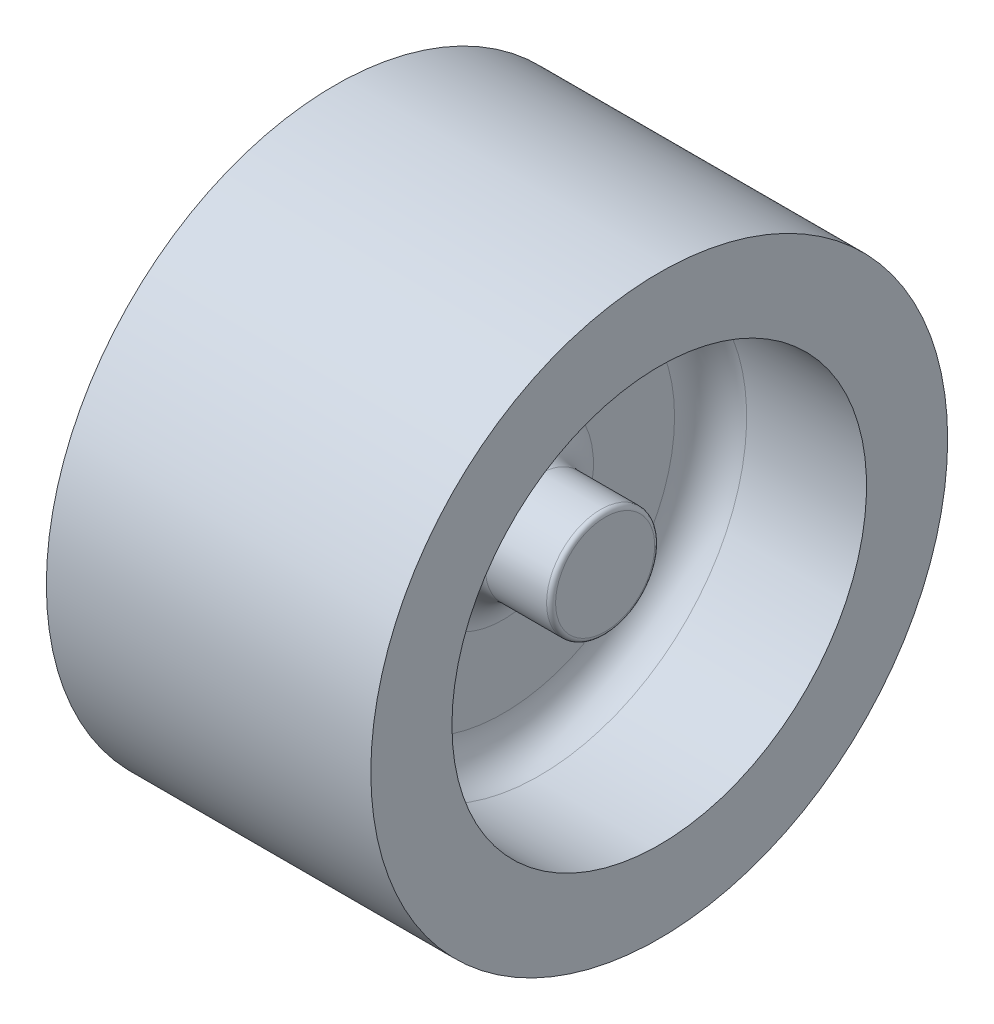
SolidWorks part; units mm, degrees
material "PE High Density"
ref_plane "Front Plane" through (0, 0, 0) normal (0, 0, 1) x (1, 0, 0)
ref_plane "Top Plane" through (0, 0, 0) normal (0, 1, 0) x (1, 0, 0)
ref_plane "Right Plane" through (0, 0, 0) normal (1, 0, 0) x (0, 0, -1)
sketch "Sketch1" plane through (0, 0, 0) normal (0, 0, 1) x (1, 0, 0)
  line L0 (0, 0) -> (14.6475, 0) construction
  line L1 (14.6475, 26.8961) -> (14.6475, -4.8961) construction
  line L2 (14.6475, 11.5) -> (14.6475, 16)
  line L3 (-3.3525, 16) -> (14.6475, 16)
  line L4 (14.6475, 11.5) -> (7.9975, 11.5)
  line L5 (0.3975, 4.5) -> (0.3975, 3.375)
  line L6 (0.1475, 3.125) -> (-4.3525, 3.125)
  line L7 (-4.3525, 3.125) -> (-4.3525, 0)
  line L8 (11.6475, 0) -> (-4.3525, 0)
  line L9 (4.3975, 13) -> (11.1475, 13)
  line L10 (11.1475, 13) -> (11.1475, 14.25)
  line L11 (2.3975, 11) -> (2.3975, 5)
  line L12 (2.1475, 4.75) -> (0.6475, 4.75)
  line L13 (11.3975, 3) -> (7.9975, 3)
  line L14 (5.9975, 5) -> (5.9975, 9.5)
  line L15 (11.6475, 2.75) -> (11.6475, 0)
  line L16 (11.1475, 14.25) -> (-3.3525, 14.25)
  line L17 (-3.3525, 14.25) -> (-3.3525, 16)
  arc A1 (5.9975, 5) -> (7.9975, 3) centre (7.9975, 5) ccw
  arc A2 (5.9975, 9.5) -> (7.9975, 11.5) centre (7.9975, 9.5) cw
  arc A3 (11.3975, 3) -> (11.6475, 2.75) centre (11.3975, 2.75) cw
  arc A4 (2.3975, 5) -> (2.1475, 4.75) centre (2.1475, 5) cw
  arc A5 (0.3975, 3.375) -> (0.1475, 3.125) centre (0.1475, 3.375) cw
  arc A6 (0.3975, 4.5) -> (0.6475, 4.75) centre (0.6475, 4.5) cw
  arc A7 (2.3975, 11) -> (4.3975, 13) centre (4.3975, 11) cw
  point P26 (2.3975, 13)
  point P32 (11.6475, 3)
  point P36 (2.3975, 4.75)
  point P40 (0.3975, 3.125)
  point P43 (0.3975, 4.75)
  dimension "D4" = 4.75
  dimension "D8" = 2
  dimension "D1" = 3.125
  dimension "D10" = 18
  dimension "D11" = 1.75
  dimension "D5" = 4.75
  dimension "D9" = 2
  dimension "D2" = 16
  dimension "D3" = 3
  dimension "D6" = 2
  dimension "D7" = 8.25
  dimension "D12" = 14.5
  dimension "D13" = 16
  dimension "D16" = 19
revolve "Revolve1" add sketch "Sketch1" angle 360 about L0
sketch "Sketch2" plane through (-4.3525, 0, 0) normal (-1, 0, 0) x (0, 0, 1)
  circle A0 centre (0, 0) radius 1.55
  dimension "D1" = 3.1
extrude "Cut-Extrude1" cut sketch "Sketch2" against normal blind 15
